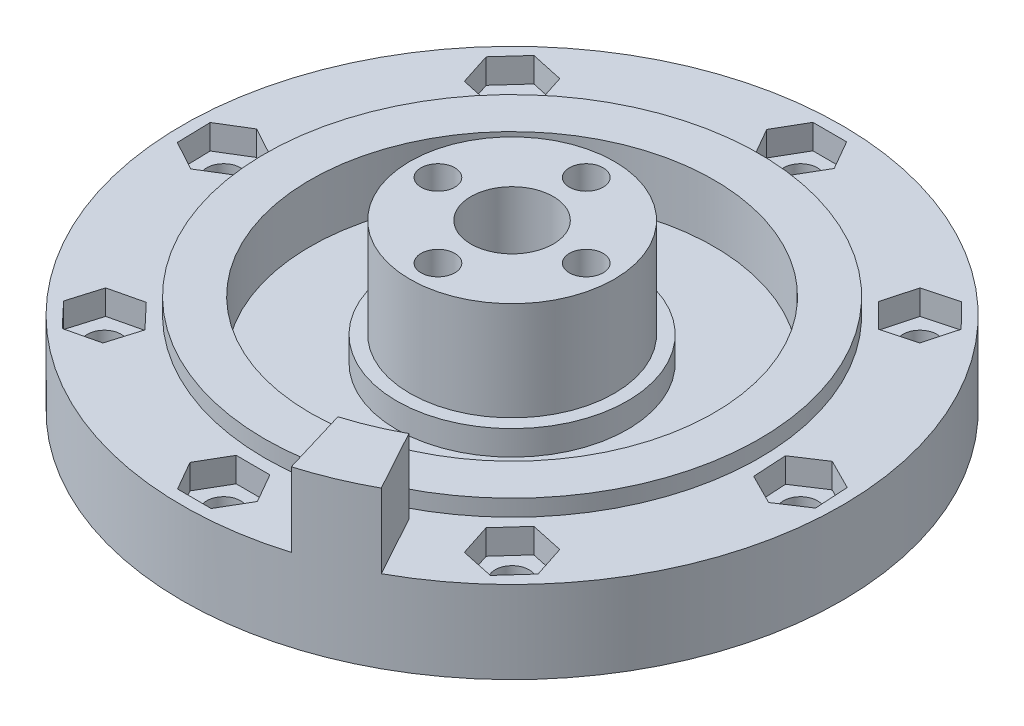
SolidWorks part; units mm, degrees
ref_plane "Front Plane" through (0, 0, 0) normal (0, 0, 1) x (1, 0, 0)
ref_plane "Top Plane" through (0, 0, 0) normal (0, 1, 0) x (1, 0, 0)
ref_plane "Right Plane" through (0, 0, 0) normal (1, 0, 0) x (0, 0, -1)
sketch "Sketch1" plane through (0, 0, 0) normal (0, 1, 0) x (1, 0, 0)
  circle A0 centre (0, 0) radius 40
  dimension "D1" = 80
extrude "Boss-Extrude1" add sketch "Sketch1" along normal blind 10
sketch "Sketch2" plane through (0, 10, 0) normal (0, 1, 0) x (1, 0, 0)
  circle A0 centre (0, 0) radius 24.5
  dimension "D1" = 49
extrude "Cut-Extrude1" cut sketch "Sketch2" against normal blind 5
sketch "Sketch3" plane through (0, 10, 0) normal (0, 1, 0) x (1, 0, 0)
  circle A0 centre (0, 0) radius 24.5
  circle A1 centre (0, 0) radius 30
  dimension "D1" = 60
extrude "Boss-Extrude2" add sketch "Sketch3" along normal blind 2
sketch "Sketch4" plane through (0, 5, 0) normal (0, 1, 0) x (1, 0, 0)
  circle A0 centre (0, 0) radius 14
  dimension "D1" = 28
extrude "Boss-Extrude3" add sketch "Sketch4" along normal blind 3 contours A0
sketch "Sketch5" plane through (0, 8, 0) normal (0, 1, 0) x (1, 0, 0)
  circle A0 centre (0, 0) radius 12.4
  dimension "D1" = 24.8
extrude "Boss-Extrude4" add sketch "Sketch5" along normal blind 12 contours A0
sketch "Sketch6" plane through (0, 20, 0) normal (0, 1, 0) x (1, 0, 0)
  circle A0 centre (0, 0) radius 9 construction
  circle A1 centre (-9, 0) radius 2.05
  circle A2 centre (0, 9) radius 2.05
  circle A3 centre (9, 0) radius 2.05
  circle A4 centre (0, -9) radius 2.05
  dimension "D1" = 4.1
  dimension "D2" = 18
extrude "Cut-Extrude2" cut sketch "Sketch6" against normal through all
sketch "Sketch7" plane through (0, 20, 0) normal (0, 1, 0) x (1, 0, 0)
  circle A0 centre (0, 0) radius 5
  dimension "D1" = 10
extrude "Cut-Extrude3" cut sketch "Sketch7" against normal through all
sketch "Sketch9" plane through (0, 10, 0) normal (0, 1, 0) x (1, 0, 0)
  line L0 (0, 35) -> (0, 0) construction
  line L1 (-24.7487, 24.7487) -> (24.7487, -24.7487) construction
  line L2 (24.7487, 24.7487) -> (-24.7487, -24.7487) construction
  circle A0 centre (0, 0) radius 35 construction
  circle A1 centre (0, 35) radius 2.05
  circle A2 centre (35, 0) radius 2.05
  circle A3 centre (0, -35) radius 2.05
  circle A4 centre (-35, 0) radius 2.05
  circle A5 centre (-24.7487, 24.7487) radius 2.05
  circle A6 centre (24.7487, 24.7487) radius 2.05
  circle A7 centre (24.7487, -24.7487) radius 2.05
  circle A8 centre (-24.7487, -24.7487) radius 2.05
  dimension "D1" = 70
  dimension "D4" = 4.1
  dimension "D2" = 45
  dimension "D3" = 45
extrude "Cut-Extrude6" cut sketch "Sketch9" against normal up to next
sketch "Sketch10" plane through (0, 10, 0) normal (0, 1, 0) x (1, 0, 0)
  line L1 (2.0443, 31.4469) -> (4.0992, 34.9939)
  line L2 (4.0992, 34.9939) -> (2.0549, 38.5469)
  line L3 (2.0549, 38.5469) -> (-2.0443, 38.5531)
  line L4 (-2.0443, 38.5531) -> (-4.0992, 35.0061)
  line L5 (-4.0992, 35.0061) -> (-2.0549, 31.4531)
  line L6 (-2.0549, 31.4531) -> (2.0443, 31.4469)
  line L7 (23.6807, 20.7911) -> (27.6421, 21.845)
  line L8 (27.6421, 21.845) -> (28.7101, 25.8026)
  line L9 (28.7101, 25.8026) -> (25.8168, 28.7063)
  line L10 (25.8168, 28.7063) -> (21.8554, 27.6525)
  line L11 (21.8554, 27.6525) -> (20.7873, 23.6949)
  line L12 (20.7873, 23.6949) -> (23.6807, 20.7911)
  line L13 (31.5734, -2.2499) -> (35.2352, -4.0924)
  line L14 (35.2352, -4.0924) -> (38.6618, -1.8425)
  line L15 (38.6618, -1.8425) -> (38.4266, 2.2499)
  line L16 (38.4266, 2.2499) -> (34.7648, 4.0924)
  line L17 (34.7648, 4.0924) -> (31.3382, 1.8425)
  line L18 (31.3382, 1.8425) -> (31.5734, -2.2499)
  line L19 (20.7398, -23.8933) -> (22.0035, -27.7929)
  line L20 (22.0035, -27.7929) -> (26.0124, -28.6483)
  line L21 (26.0124, -28.6483) -> (28.7577, -25.6042)
  line L22 (28.7577, -25.6042) -> (27.494, -21.7046)
  line L23 (27.494, -21.7046) -> (23.4851, -20.8492)
  line L24 (23.4851, -20.8492) -> (20.7398, -23.8933)
  line L25 (2.0583, -31.455) -> (-2.0409, -31.445)
  line L26 (-2.0409, -31.445) -> (-4.0992, -34.99)
  line L27 (-4.0992, -34.99) -> (-2.0583, -38.545)
  line L28 (-2.0583, -38.545) -> (2.0409, -38.555)
  line L29 (2.0409, -38.555) -> (4.0992, -35.01)
  line L30 (4.0992, -35.01) -> (2.0583, -31.455)
  line L31 (-20.7609, -23.7999) -> (-23.5765, -20.8207)
  line L32 (-23.5765, -20.8207) -> (-27.5644, -21.7695)
  line L33 (-27.5644, -21.7695) -> (-28.7366, -25.6975)
  line L34 (-28.7366, -25.6975) -> (-25.921, -28.6767)
  line L35 (-25.921, -28.6767) -> (-21.9331, -27.7279)
  line L36 (-21.9331, -27.7279) -> (-20.7609, -23.7999)
  line L37 (-31.3991, -1.9587) -> (-31.5032, 2.1391)
  line L38 (-31.5032, 2.1391) -> (-35.1041, 4.0979)
  line L39 (-35.1041, 4.0979) -> (-38.6009, 1.9587)
  line L40 (-38.6009, 1.9587) -> (-38.4968, -2.1391)
  line L41 (-38.4968, -2.1391) -> (-34.8959, -4.0979)
  line L42 (-34.8959, -4.0979) -> (-31.3991, -1.9587)
  line L43 (-23.4953, 20.8459) -> (-20.742, 23.8829)
  line L44 (-20.742, 23.8829) -> (-21.9955, 27.7857)
  line L45 (-21.9955, 27.7857) -> (-26.0022, 28.6516)
  line L46 (-26.0022, 28.6516) -> (-28.7554, 25.6146)
  line L47 (-28.7554, 25.6146) -> (-27.502, 21.7118)
  line L48 (-27.502, 21.7118) -> (-23.4953, 20.8459)
  circle A0 centre (0, 35) radius 3.55 construction
  circle A1 centre (24.7487, 24.7487) radius 3.55 construction
  circle A2 centre (35, 0) radius 3.55 construction
  circle A3 centre (24.7487, -24.7487) radius 3.55 construction
  circle A4 centre (0, -35) radius 3.55 construction
  circle A5 centre (-24.7487, -24.7487) radius 3.55 construction
  circle A6 centre (-35, 0) radius 3.55 construction
  circle A7 centre (-24.7487, 24.7487) radius 3.55 construction
  point P55 (36.5957, 3.1712)
  point P64 (3.07, -36.7825)
  dimension "D1" = 7.1
  dimension "D2" = 7.1
  dimension "D3" = 7.1
  dimension "D4" = 7.1
  dimension "D5" = 7.1
  dimension "D6" = 7.1
  dimension "D7" = 7.1
  dimension "D8" = 7.1
extrude "Cut-Extrude7" cut sketch "Sketch10" against normal blind 3
sketch "Sketch11" plane through (0, 10, 0) normal (0, 1, 0) x (1, 0, 0)
  line L0 (9.0806, -30.219) -> (11.5113, -38.3078)
  line L1 (15.1538, -27.6768) -> (19.2102, -35.0852)
  arc A0 (11.5113, -38.3078) -> (19.2102, -35.0852) centre (0, 0) ccw
  arc A1 (9.0806, -30.219) -> (15.1538, -27.6768) centre (0, 0) ccw
extrude "Boss-Extrude5" add sketch "Sketch11" along normal blind 9
